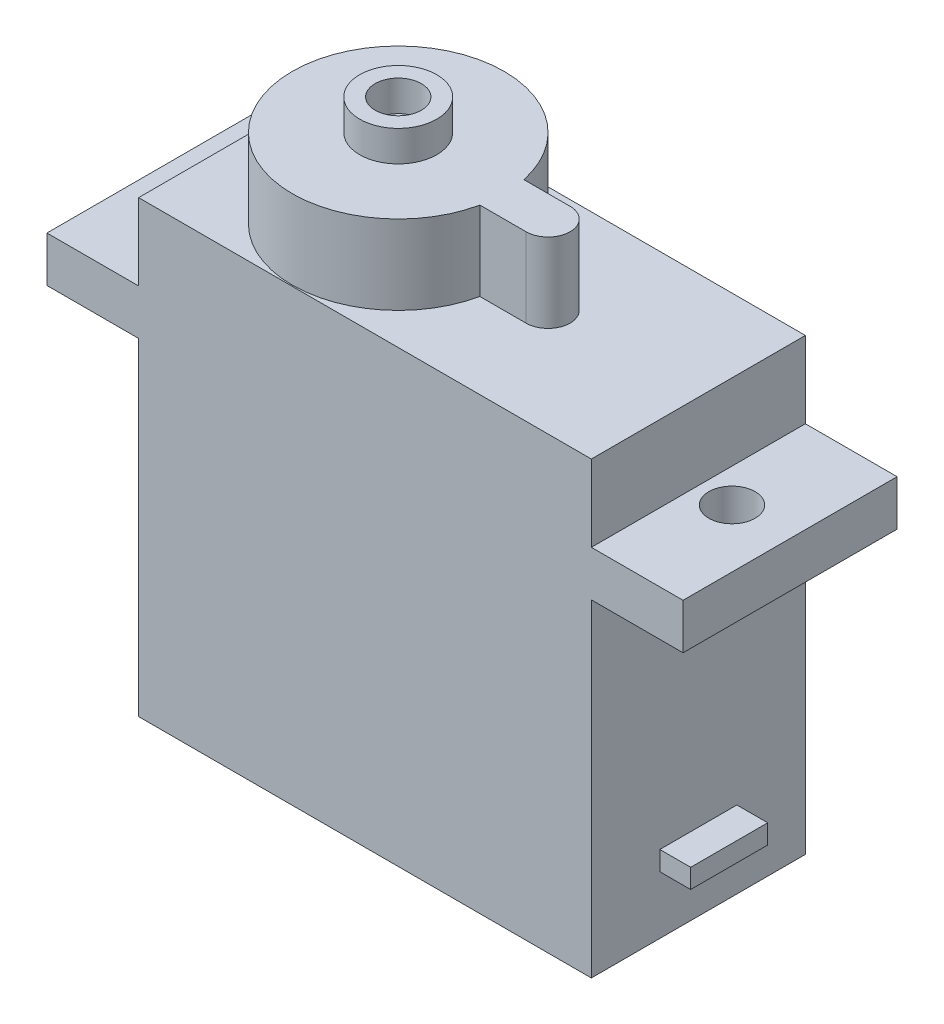
SolidWorks part; units mm, degrees
material "Chrome Stainless Steel"
ref_plane "Front Plane" through (0, 0, 0) normal (0, 0, 1) x (1, 0, 0)
ref_plane "Top Plane" through (0, 0, 0) normal (0, 1, 0) x (1, 0, 0)
ref_plane "Right Plane" through (0, 0, 0) normal (1, 0, 0) x (0, 0, -1)
sketch "Sketch1" plane through (0, 0, 0) normal (0, 0, 1) x (1, 0, 0)
  line L0 (0, 0.6491) -> (0, -0.6694) construction
  line L1 (-0.7109, 0) -> (0.7041, 0) construction
  line L2 (-58.75, 0) -> (58.75, 0)
  line L3 (58.75, 0) -> (58.75, 85)
  line L4 (58.75, 85) -> (82.55, 85)
  line L5 (82.55, 85) -> (82.55, 96.8)
  line L6 (82.55, 96.8) -> (58.75, 96.8)
  line L7 (58.75, 96.8) -> (58.75, 116.65)
  line L8 (58.75, 116.65) -> (-58.75, 116.65)
  line L9 (-58.75, 116.65) -> (-58.75, 96.8)
  line L10 (-58.75, 96.8) -> (-82.55, 96.8)
  line L11 (-82.55, 96.8) -> (-82.55, 85)
  line L12 (-82.55, 85) -> (-58.75, 85)
  line L13 (-58.75, 85) -> (-58.75, 0)
  dimension "D1" = 117.5
  dimension "D2" = 23.8
  dimension "D3" = 11.8
  dimension "D4" = 85
  dimension "D5" = 19.85
extrude "Boss-Extrude1" add sketch "Sketch1" along normal mid plane 55.55
sketch "Sketch2" plane through (0, 116.65, 0) normal (0, 1, 0) x (1, 0, 0)
  line L0 (0, 60.2477) -> (0, -56.905) construction
  line L1 (-73.0807, 0) -> (79.3727, 0) construction
  line L2 (7.7564, 5.7118) -> (19.7564, 5.7118)
  line L3 (7.7564, -5.7118) -> (19.7564, -5.7118)
  line L4 (-58.75, -27.775) -> (-58.75, 27.775) construction
  line L5 (58.75, 27.775) -> (-58.75, 27.775) construction
  circle A0 centre (-19.1439, 0) radius 27.5
  arc A1 (19.7564, -5.7118) -> (19.7564, 5.7118) centre (19.7564, 0) ccw
  dimension "D1" = 55
  dimension "D3" = 5.7118
  dimension "D2" = 12
  dimension "D4" = 39.6061
extrude "Boss-Extrude2" add sketch "Sketch2" along normal blind 20.55 contours L3 A1 L2 A0 | A0
sketch "Sketch3" plane through (0, 137.2, 0) normal (0, 1, 0) x (1, 0, 0)
  circle A0 centre (-19.1439, 0) radius 6
  dimension "D1" = 12
extrude "Extrude-Thin1" add sketch "Sketch3" along normal blind 8 thin
sketch "Sketch4" plane through (0, 96.8, 0) normal (0, 1, 0) x (1, 0, 0)
  line L1 (0, 50.2341) -> (0, -41.3633) construction
  circle A0 centre (67.475, 0) radius 6
  circle A2 centre (-67.475, 0) radius 6
  dimension "D1" = 12
  dimension "D2" = 134.95
extrude "Cut-Extrude2" cut sketch "Sketch4" against normal up to surface (11.8 mm away) up to face at (70.65, 85, 0)
sketch "Sketch5" plane through (58.75, 0, 0) normal (1, 0, 0) x (0, 0, -1)
  line L0 (-27.775, 0) -> (27.775, 0) construction
  line L1 (-10, 20) -> (10, 20)
  line L2 (-10, 20) -> (-10, 15)
  line L3 (-10, 15) -> (10, 15)
  line L4 (10, 20) -> (10, 15)
  line L5 (-10, 20) -> (10, 15) construction
  line L6 (-10, 15) -> (10, 20) construction
  point P0 (0, 17.5)
  dimension "D1" = 5
  dimension "D2" = 20
  dimension "D3" = 15
extrude "Boss-Extrude3" add sketch "Sketch5" along normal blind 8
mirror "Mirror1" about plane through (0, 0, 0) normal (1, 0, 0) of "Boss-Extrude3"
